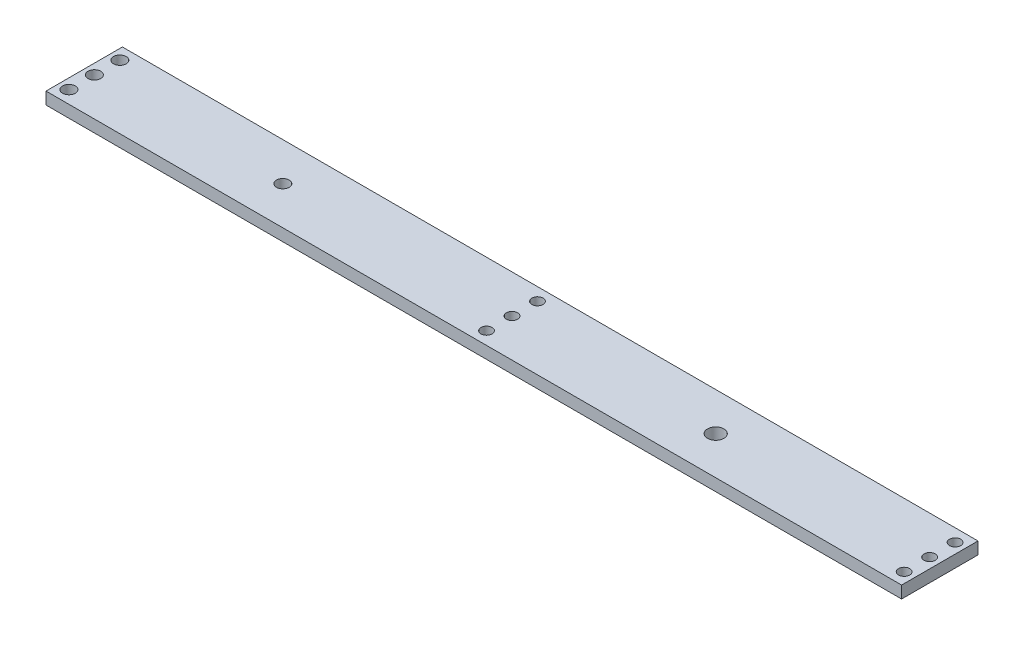
SolidWorks part; units mm, degrees
material "ABS"
ref_plane "Plano frontal" through (0, 0, 0) normal (0, 0, 1) x (1, 0, 0)
ref_plane "Plano superior" through (0, 0, 0) normal (0, 1, 0) x (1, 0, 0)
ref_plane "Plano direito" through (0, 0, 0) normal (1, 0, 0) x (0, 0, -1)
sketch "Esboço1" plane through (0, 0, 0) normal (0, 1, 0) x (1, 0, 0)
  line L0 (0, 0) -> (160, 0) construction
  line L1 (160, -15) -> (-160, -15)
  line L2 (160, -15) -> (160, 15) construction
  line L3 (160, 15) -> (-160, 15)
  line L4 (-160, -15) -> (-160, 15) construction
  line L5 (160, -15) -> (-160, 15) construction
  line L6 (160, 15) -> (-160, -15) construction
  line L7 (-164, 15) -> (-164, 5) construction
  line L8 (-168, 15) -> (-160, 15)
  line L9 (-168, 15) -> (-168, -15)
  line L10 (-168, -15) -> (-160, -15)
  line L11 (-160, 15) -> (-160, -15) construction
  line L12 (-164, 5) -> (-164, -5) construction
  line L13 (-164, -5) -> (-164, -15) construction
  line L15 (0, 15) -> (0, 5) construction
  line L16 (0, 5) -> (0, -5) construction
  line L17 (0, -5) -> (0, -15) construction
  line L18 (0, 0) -> (-90, 0) construction
  line L19 (164, 15) -> (164, 5) construction
  line L20 (160, 15) -> (168, 15)
  line L21 (160, 15) -> (160, -15)
  line L22 (160, -15) -> (168, -15)
  line L23 (168, 15) -> (168, -15)
  line L24 (164, 5) -> (164, -5) construction
  line L25 (164, -5) -> (164, -15) construction
  circle A0 centre (80, 0) radius 3.225
  circle A1 centre (-164, 10) radius 2.5
  circle A2 centre (-164, 0) radius 2.5
  circle A3 centre (-164, -10) radius 2.5
  circle A4 centre (0, 10) radius 2.2
  circle A5 centre (0, 0) radius 2.2
  circle A6 centre (0, -10) radius 2.2
  circle A7 centre (164, 10) radius 2.2
  circle A8 centre (164, 0) radius 2.2
  circle A9 centre (164, -10) radius 2.2
  circle A10 centre (-90, 0) radius 2.5
  point P0 (0, 0)
  point P15 (-160, 0)
  point P16 (-160, 0)
  dimension "D2" = 6.45
  dimension "D5" = 5
  dimension "D6" = 4.4
  dimension "D9" = 4.4
  dimension "D10" = 5
  dimension "D1" = 160
  dimension "D3" = 30
  dimension "D4" = 8
  dimension "D7" = 170
  dimension "D8" = 8
extrude "Ressalto-extrusão1" add sketch "Esboço1" along normal blind 4.7625 contours L21 L3 L8 L9 L10 L1 A6 A5 A4 A3 A2 A1 A0 | L23 L20 L21 L22 A9 A8 A7
